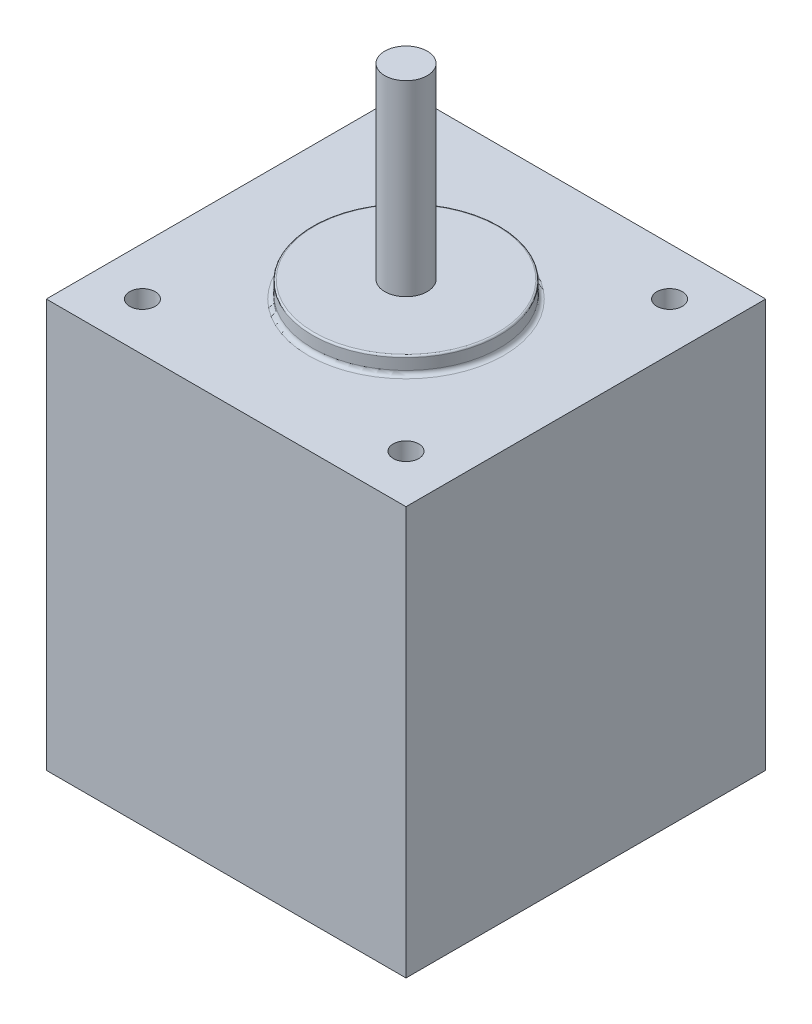
SolidWorks part; units mm, degrees
ref_plane "Front Plane" through (0, 0, 0) normal (0, 0, 1) x (1, 0, 0)
ref_plane "Top Plane" through (0, 0, 0) normal (0, 1, 0) x (1, 0, 0)
ref_plane "Right Plane" through (0, 0, 0) normal (1, 0, 0) x (0, 0, -1)
sketch "Sketch1" plane through (0, 0, 0) normal (0, 1, 0) x (1, 0, 0)
  line L1 (-15.5, 15.5) -> (15.5, 15.5) construction
  line L2 (-15.5, 15.5) -> (-15.5, -15.5) construction
  line L3 (-15.5, -15.5) -> (15.5, -15.5) construction
  line L4 (15.5, 15.5) -> (15.5, -15.5) construction
  line L5 (-15.5, 15.5) -> (15.5, -15.5) construction
  line L6 (-15.5, -15.5) -> (15.5, 15.5) construction
  line L7 (-21.15, 21.15) -> (21.15, 21.15)
  line L8 (-21.15, 21.15) -> (-21.15, -21.15)
  line L9 (-21.15, -21.15) -> (21.15, -21.15)
  line L10 (21.15, 21.15) -> (21.15, -21.15)
  line L11 (-21.15, 21.15) -> (21.15, -21.15) construction
  line L12 (-21.15, -21.15) -> (21.15, 21.15) construction
  circle A0 centre (15.5, 15.5) radius 1.5
  circle A1 centre (-15.5, 15.5) radius 1.5
  circle A2 centre (-15.5, -15.5) radius 1.5
  circle A3 centre (15.5, -15.5) radius 1.5
  point P0 (0, 0)
  point P6 (0, 0)
  dimension "D3" = 3
  dimension "D1" = 31
  dimension "D2" = 42.3
extrude "Boss-Extrude1" add sketch "Sketch1" against normal blind 48
sketch "Sketch2" plane through (0, 0, 0) normal (0, 1, 0) x (1, 0, 0)
  circle A0 centre (0, 0) radius 11
  dimension "D1" = 22
extrude "Boss-Extrude2" add sketch "Sketch2" along normal blind 2
sketch "Sketch3" plane through (0, 0, 0) normal (0, 1, 0) x (1, 0, 0)
  circle A0 centre (0, 0) radius 2.5
  dimension "D1" = 5
extrude "Boss-Extrude3" add sketch "Sketch3" along normal blind 24
fillet "Fillet1" radius 0.5 1 edges at (0, 0, 11)
fillet "Fillet2" radius 0.2 1 edges at (0, 2, 11)
